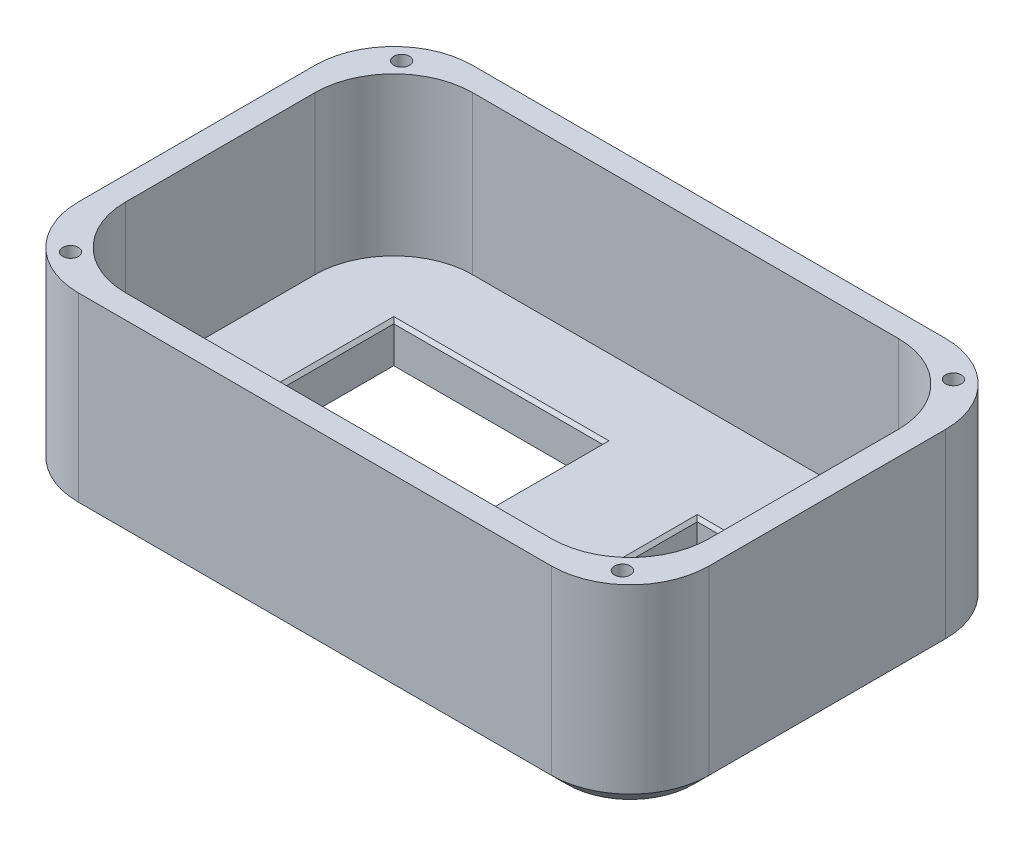
SolidWorks part; units mm, degrees
ref_plane "Front Plane" through (0, 0, 0) normal (0, 0, 1) x (1, 0, 0)
ref_plane "Top Plane" through (0, 0, 0) normal (0, 1, 0) x (1, 0, 0)
ref_plane "Right Plane" through (0, 0, 0) normal (1, 0, 0) x (0, 0, -1)
sketch "Sketch1" plane through (0, 0, 0) normal (0, 1, 0) x (1, 0, 0)
  line L1 (-40, 25) -> (40, 25)
  line L2 (-40, 25) -> (-40, -25)
  line L3 (-40, -25) -> (40, -25)
  line L4 (40, 25) -> (40, -25)
  line L5 (-40, 25) -> (40, -25) construction
  line L6 (-40, -25) -> (40, 25) construction
  point P0 (0, 0)
  dimension "D1" = 80
  dimension "D2" = 50
extrude "Boss-Extrude1" add sketch "Sketch1" along normal blind 25
sketch "Sketch2" plane through (0, 25, 0) normal (0, 1, 0) x (1, 0, 0)
  line L0 (40, 25) -> (-40, 25) construction
  line L1 (37, 22) -> (-37, 22)
  line L2 (37, 22) -> (37, -22)
  line L3 (37, -22) -> (-37, -22)
  line L4 (-37, 22) -> (-37, -22)
  line L5 (37, 22) -> (-37, -22) construction
  line L6 (37, -22) -> (-37, 22) construction
  line L7 (-40, 25) -> (-40, -25) construction
  point P0 (0, 0)
  dimension "D1" = 3
  dimension "D2" = 3
extrude "Cut-Extrude1" cut sketch "Sketch2" against normal blind 20
sketch "Sketch3" plane through (0, 5, 0) normal (0, 1, 0) x (1, 0, 0)
  line L0 (-37, 22) -> (-37, -22) construction
  line L1 (-27, 12) -> (-0.5, 12)
  line L2 (-27, 12) -> (-27, -9)
  line L3 (-27, -9) -> (-0.5, -9)
  line L4 (-0.5, 12) -> (-0.5, -9)
  line L5 (37, 22) -> (-37, 22) construction
  dimension "D1" = 26.5
  dimension "D2" = 21
  dimension "D3" = 10
  dimension "D4" = 10
extrude "Cut-Extrude2" cut sketch "Sketch3" against normal blind 6
sketch "Sketch4" plane through (0, 5, 0) normal (0, 1, 0) x (1, 0, 0)
  line L0 (37, 22) -> (-37, 22) construction
  line L1 (14, 9.5) -> (27, 9.5)
  line L2 (14, 9.5) -> (14, -7)
  line L3 (14, -7) -> (27, -7)
  line L4 (27, 9.5) -> (27, -7)
  line L5 (37, -22) -> (37, 22) construction
  dimension "D1" = 16.5
  dimension "D2" = 13
  dimension "D3" = 12.5
  dimension "D4" = 10
extrude "Cut-Extrude3" cut sketch "Sketch4" against normal blind 6
fillet "Fillet1" radius 10 4 edges at (40, 12.5, 25) (40, 12.5, -25) (-40, 12.5, -25) (-40, 12.5, 25)
sketch "Sketch5" plane through (0, 0, 0) normal (0, -1, 0) x (1, 0, 0)
  text T0 "Weather Machine" font "Century Gothic" height in points 22
extrude "Cut-Extrude4" cut sketch "Sketch5" against normal blind 1
chamfer "Chamfer1" distance 2 angle 45 8 edges at (0, 0, -25) (40, 0, 0) (37.0711, 0, -22.0711) (37.0711, 0, 22.0711) (0, 0, 25) (-37.0711, 0, -22.0711) (-37.0711, 0, 22.0711) (-40, 0, 0)
fillet "Fillet2" radius 10 4 edges at (37, 15, -22) (-37, 15, -22) (-37, 15, 22) (37, 15, 22)
chamfer "Chamfer2" distance 0.4 angle 45 8 edges at (-27, 5, -1.5) (-13.75, 5, -12) (-0.5, 5, -1.5) (-13.75, 5, 9) (14, 5, -1.25) (20.5, 5, -9.5) (20.5, 5, 7) (27, 5, -1.25)
sketch "Sketch6" plane through (0, 25, 0) normal (0, 1, 0) x (1, 0, 0)
  line L0 (-13.75, 0) -> (13.75, 0) construction
  line L1 (0, -13.75) -> (0, 13.75) construction
  circle A0 centre (-35, 21) radius 1
  circle A1 centre (-35, -21) radius 1
  circle A2 centre (35, -21) radius 1
  circle A3 centre (35, 21) radius 1
  dimension "D1" = 2
  dimension "D2" = 35
  dimension "D3" = 21
extrude "Cut-Extrude5" cut sketch "Sketch6" against normal blind 5
